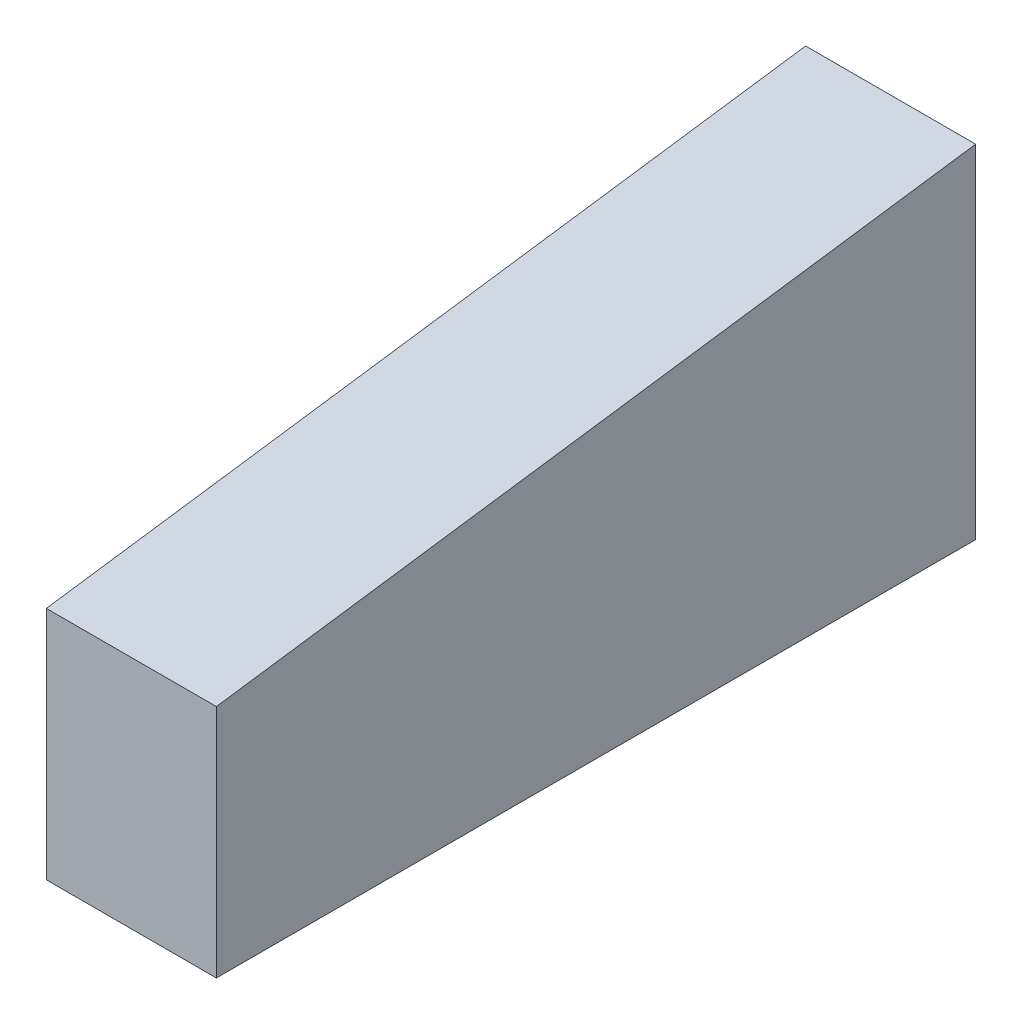
SolidWorks part; units mm, degrees
ref_plane "Front" through (0, 0, 0) normal (0, 0, 1) x (1, 0, 0)
ref_plane "Top" through (0, 0, 0) normal (0, 1, 0) x (1, 0, 0)
ref_plane "Right" through (0, 0, 0) normal (1, 0, 0) x (0, 0, -1)
sketch "Sketch1" plane through (0, 0, 0) normal (0, 1, 0) x (1, 0, 0)
  line L1 (-24.8247, -110.8486) -> (24.8247, -110.8486)
  line L2 (-24.8247, -110.8486) -> (-24.8247, 110.8486)
  line L3 (-24.8247, 110.8486) -> (24.8247, 110.8486)
  line L4 (24.8247, -110.8486) -> (24.8247, 110.8486)
  line L5 (-24.8247, -110.8486) -> (24.8247, 110.8486) construction
  line L6 (-24.8247, 110.8486) -> (24.8247, -110.8486) construction
  point P0 (0, 0)
  point P6 (24.8247, 110.8486)
extrude "Boss-Extrude1" add sketch "Sketch1" along normal blind 100
sketch "Sketch2" plane through (24.8247, 0, 0) normal (1, 0, 0) x (0, 0, -1)
  line L0 (110.8486, 100) -> (-110.8486, 68.6336)
  line L1 (-110.8486, 100) -> (-110.8486, 0) construction
  line L2 (-110.8486, 68.6336) -> (-110.8486, 100)
  line L3 (-110.8486, 100) -> (110.8486, 100)
extrude "Cut-Extrude1" cut sketch "Sketch2" against normal blind 100
